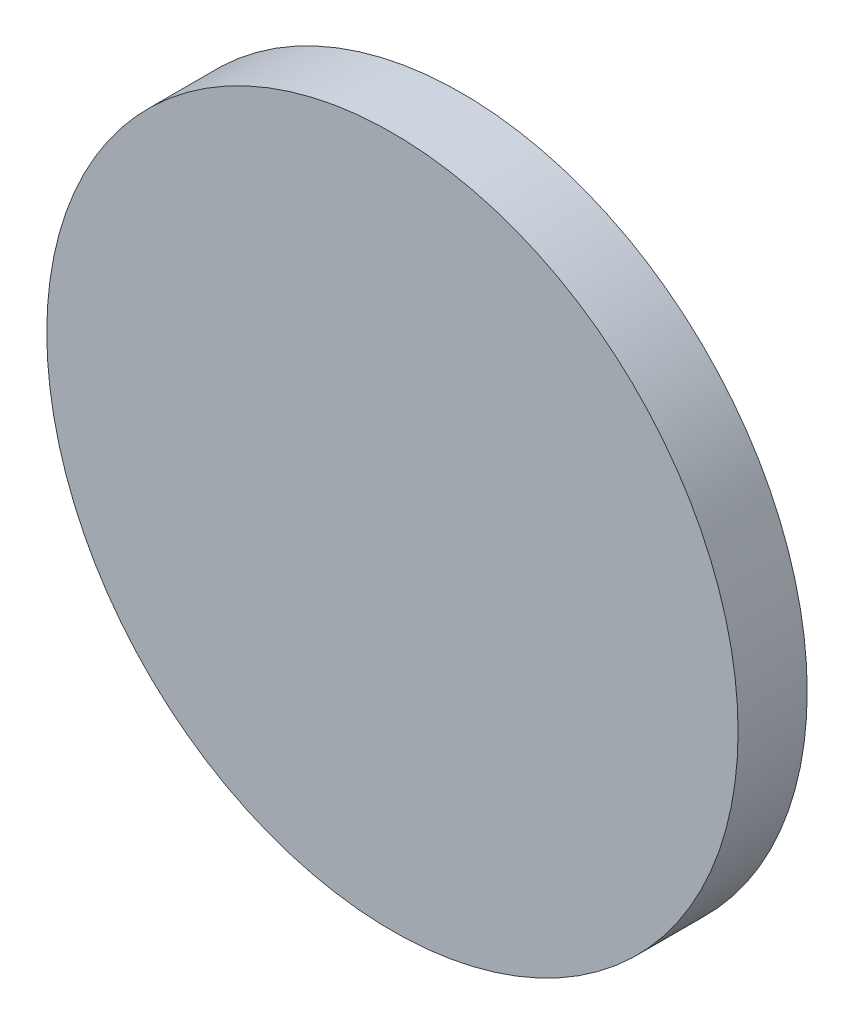
SolidWorks part; units mm, degrees
ref_plane "前视基准面" through (0, 0, 0) normal (0, 0, 1) x (1, 0, 0)
ref_plane "上视基准面" through (0, 0, 0) normal (0, 1, 0) x (1, 0, 0)
ref_plane "右视基准面" through (0, 0, 0) normal (1, 0, 0) x (0, 0, -1)
sketch "草图1" plane through (0, 0, 0) normal (0, 0, 1) x (1, 0, 0)
  circle A0 centre (0, 0) radius 500
extrude "凸台-拉伸1" add sketch "草图1" along normal blind 100
